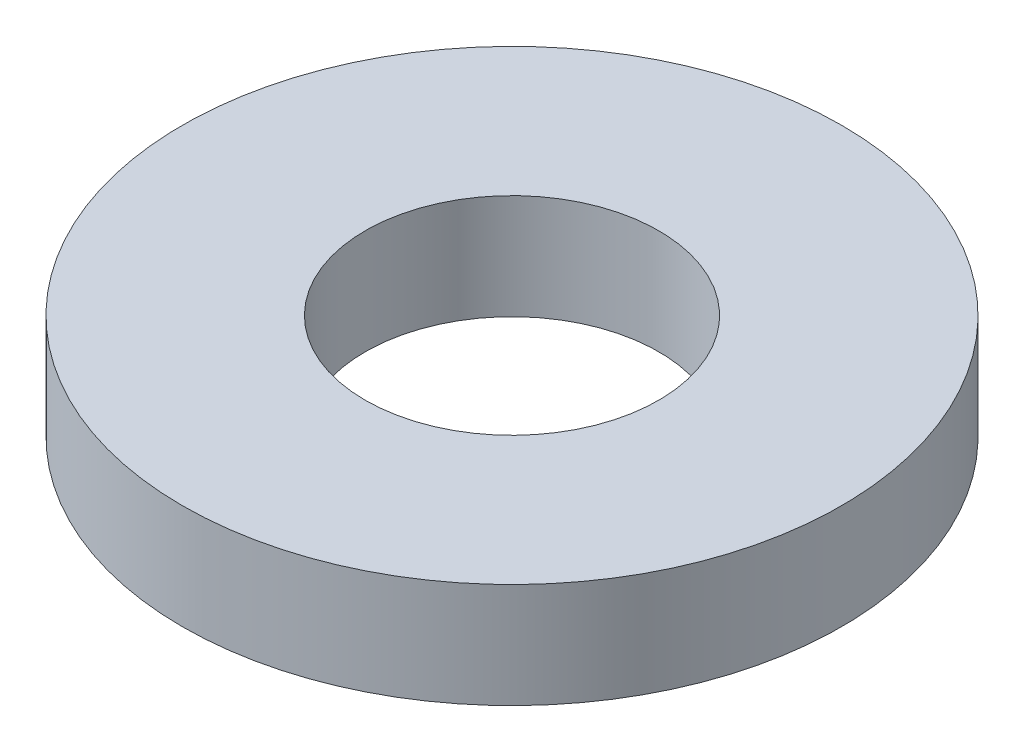
SolidWorks part; units mm, degrees
ref_plane "Front Plane" through (0, 0, 0) normal (0, 0, 1) x (1, 0, 0)
ref_plane "Top Plane" through (0, 0, 0) normal (0, 1, 0) x (1, 0, 0)
ref_plane "Right Plane" through (0, 0, 0) normal (1, 0, 0) x (0, 0, -1)
sketch "Sketch1" plane through (0, 0, 0) normal (0, 1, 0) x (1, 0, 0)
  circle A0 centre (0, 0) radius 5.588
  circle A1 centre (0, 0) radius 2.4892
  dimension "D1" = 11.176
  dimension "D2" = 4.9784
extrude "Boss-Extrude1" add sketch "Sketch1" along normal blind 1.778
equation "\"Middle Coupler Inner Daimeter\"= 6.25in"
equation "\"Middle Coupler  Wall Thickness\" = 0.25in"
equation "\"Middle Coupler Bottom Thickness\"= 0.2in"
equation "\"Bearing Rail Offset\"= 0.45in"
equation "\"3-56 UNF Tap\"= 0.089in"
equation "\"3-56 UNF Clearance\"= 0.104in"
equation "\"Ball Bearing Distance\"= 0.03in"
equation "\"TCA Outer Diameter\" = 8.625in"
equation "\"Interstage Aeroframe Wall Thickness\" = 0.072in"
equation "\"Compression Spring OD\"= 0.42in"
equation "\"D1@Sketch1\"=\"Compression Spring OD\"+0.02"
equation "\"10-24 Tap\"= 0.157in"
equation "\"10-24 Clearance\"= 0.196in"
equation "\"D2@Sketch1\"=\"10-24 Clearance\""
